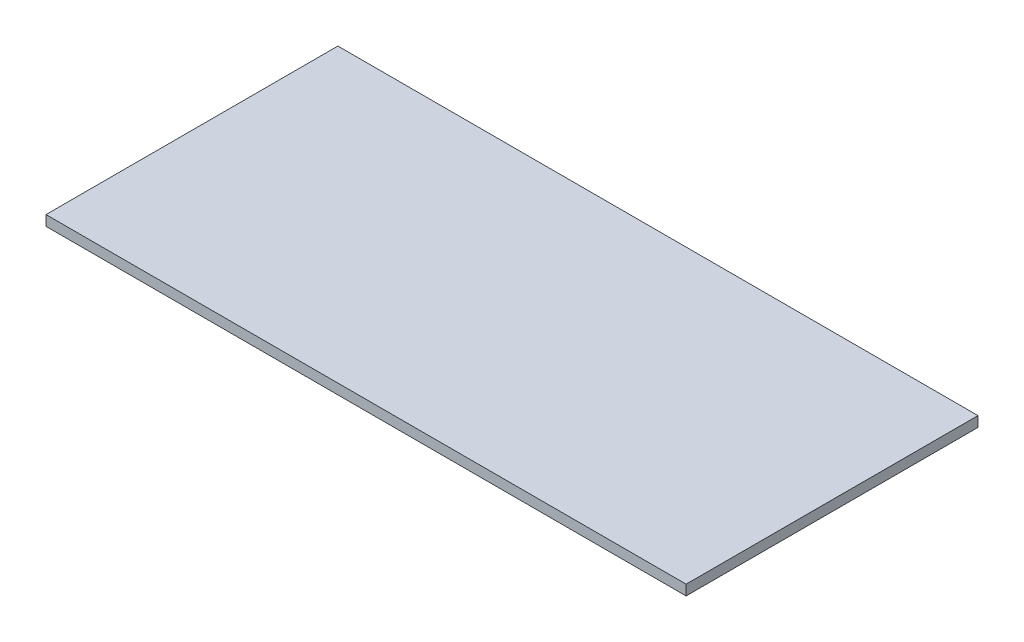
SolidWorks part; units mm, degrees
ref_plane "Front Plane" through (0, 0, 0) normal (0, 0, 1) x (1, 0, 0)
ref_plane "Top Plane" through (0, 0, 0) normal (0, 1, 0) x (1, 0, 0)
ref_plane "Right Plane" through (0, 0, 0) normal (1, 0, 0) x (0, 0, -1)
sketch "Sketch1" plane through (0, 0, 0) normal (0, 1, 0) x (1, 0, 0)
  line L1 (-128.2712, 50.7203) -> (121.7288, 50.7203)
  line L2 (-128.2712, 50.7203) -> (-128.2712, -63.2797)
  line L3 (-128.2712, -63.2797) -> (121.7288, -63.2797)
  line L4 (121.7288, 50.7203) -> (121.7288, -63.2797)
  line L5 (-128.2712, 50.7203) -> (121.7288, -63.2797) construction
  line L6 (-128.2712, -63.2797) -> (121.7288, 50.7203) construction
  point P4 (-3.2712, -6.2797)
  dimension "D1" = 114
  dimension "D2" = 250
extrude "Boss-Extrude1" add sketch "Sketch1" along normal blind 4
